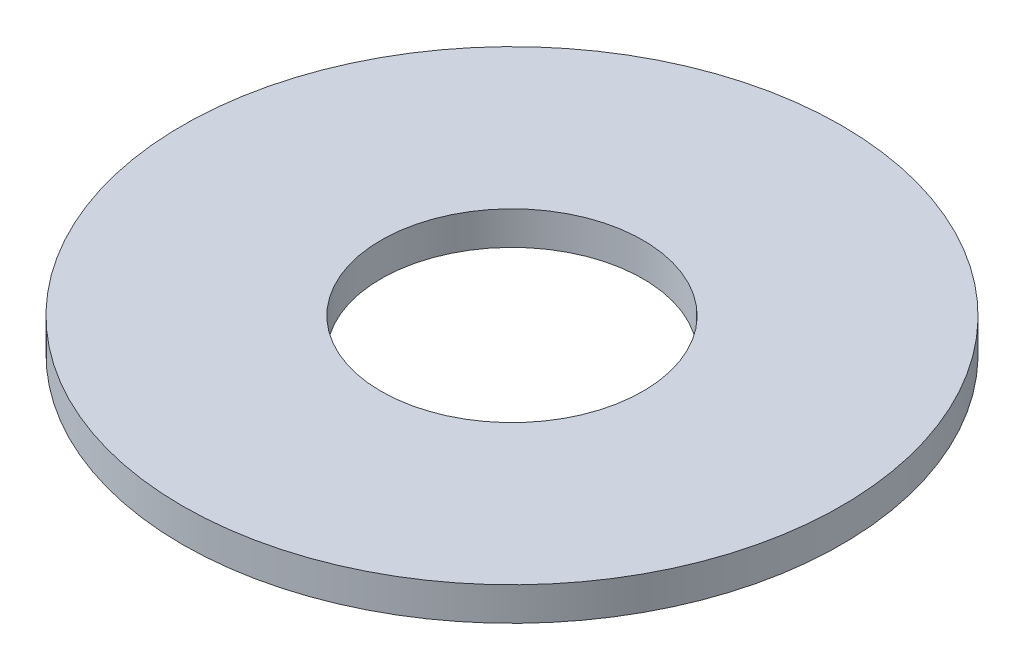
SolidWorks part; units mm, degrees
ref_plane "Front Plane" through (0, 0, 0) normal (0, 0, 1) x (1, 0, 0)
ref_plane "Top Plane" through (0, 0, 0) normal (0, 1, 0) x (1, 0, 0)
ref_plane "Right Plane" through (0, 0, 0) normal (1, 0, 0) x (0, 0, -1)
sketch "Sketch1" plane through (0, 0, 0) normal (0, 1, 0) x (1, 0, 0)
  circle A0 centre (0, 0) radius 4.7625
  dimension "OD" = 9.525
extrude "Boss-Extrude1" add sketch "Sketch1" along normal blind 0.4826
sketch "Sketch5" plane through (0, 0.4826, 0) normal (0, 1, 0) x (-1, 0, 0)
  circle A0 centre (0, 0) radius 1.8923
  dimension "ID" = 3.7846
extrude "Cut-Extrude1" cut sketch "Sketch5" against normal through all
